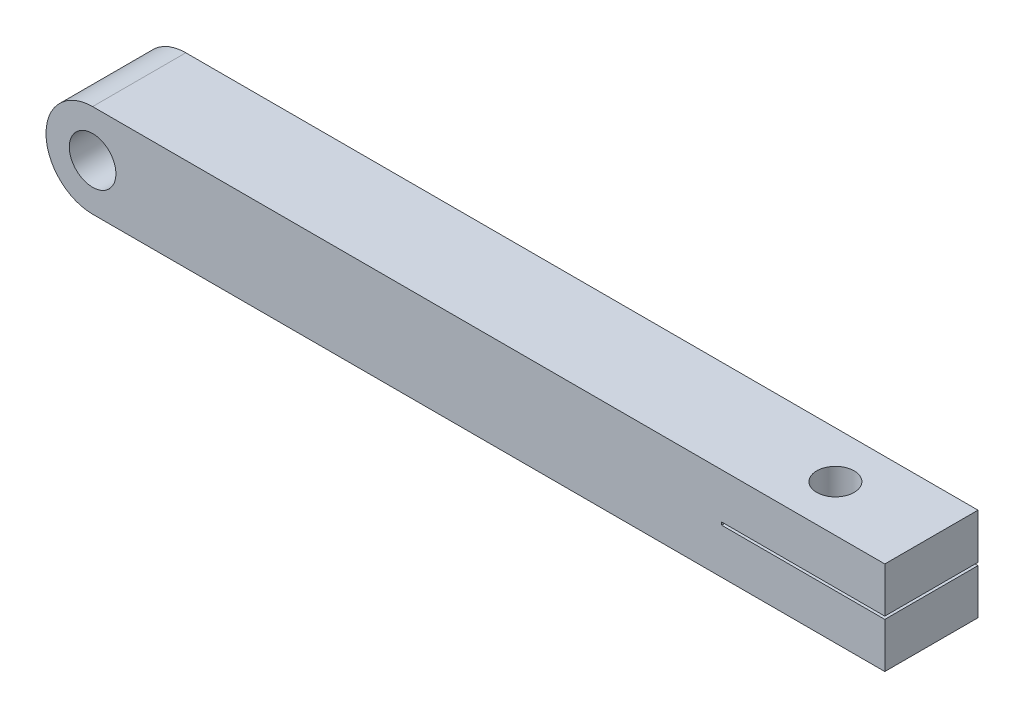
SolidWorks part; units mm, degrees
material "PET"
ref_plane "Front Plane" through (0, 0, 0) normal (0, 0, 1) x (1, 0, 0)
ref_plane "Top Plane" through (0, 0, 0) normal (0, 1, 0) x (1, 0, 0)
ref_plane "Right Plane" through (0, 0, 0) normal (1, 0, 0) x (0, 0, -1)
sketch "Sketch1" plane through (0, 0, 0) normal (0, 0, 1) x (1, 0, 0)
  line L9 (85.725, 0.1905) -> (85.725, -0.1905)
  line L11 (0, 6.35) -> (107.95, 6.35)
  line L12 (107.95, 6.35) -> (107.95, 0.1905)
  line L13 (107.95, 0.1905) -> (85.725, 0.1905)
  line L15 (0, -6.35) -> (107.95, -6.35)
  line L16 (107.95, -6.35) -> (107.95, -0.1905)
  line L18 (85.725, -0.1905) -> (107.95, -0.1905)
  circle A0 centre (0, 0) radius 3.175
  arc A9 (0, 6.35) -> (0, -6.35) centre (0, 0) ccw
  point P0 (-6.35, 0)
  point P17 (107.95, 0.1905)
  point P20 (107.95, 6.35)
  point P27 (0, 12.7)
  point P30 (0, 0)
  dimension "D6" = 6.35
  dimension "D7" = 22.225
  dimension "D1" = 114.3
  dimension "D3" = 6.35
  dimension "D4" = 12.7
  dimension "D5" = 0.381
extrude "Boss-Extrude1" add sketch "Sketch1" along normal blind 12.7
hole_wizard "#10 Clearance Hole2" positions "Sketch5" profile "Sketch6" hole size "#10" standard "ANSI Inch" end condition through all
sketch "Sketch5" plane through (0, 6.35, 0) normal (0, 1, 0) x (1, 0, 0)
  line L0 (107.95, 0) -> (0, 0) construction
  line L1 (85.725, -12.7) -> (85.725, 0) construction
  point P0 (94.869, -6.35)
  dimension "D1" = 6.35
  dimension "D2" = 9.144
sketch "Sketch6" plane through (94.869, 6.35, 6.35) normal (1, 0, 0) x (0, 0, 1)
  line L0 (0, 0) -> (0, 12.7)
  line L1 (0, 12.7) -> (2.5527, 12.7)
  line L2 (2.5527, 12.7) -> (2.5527, 0)
  line L5 (2.5527, 0) -> (0, 0)
  line L11 (0, -6.35) -> (0, 107.95) construction
  dimension "Thru Hole Dia." = 5.1054
  dimension "Thru Hole Depth" = 12.7
